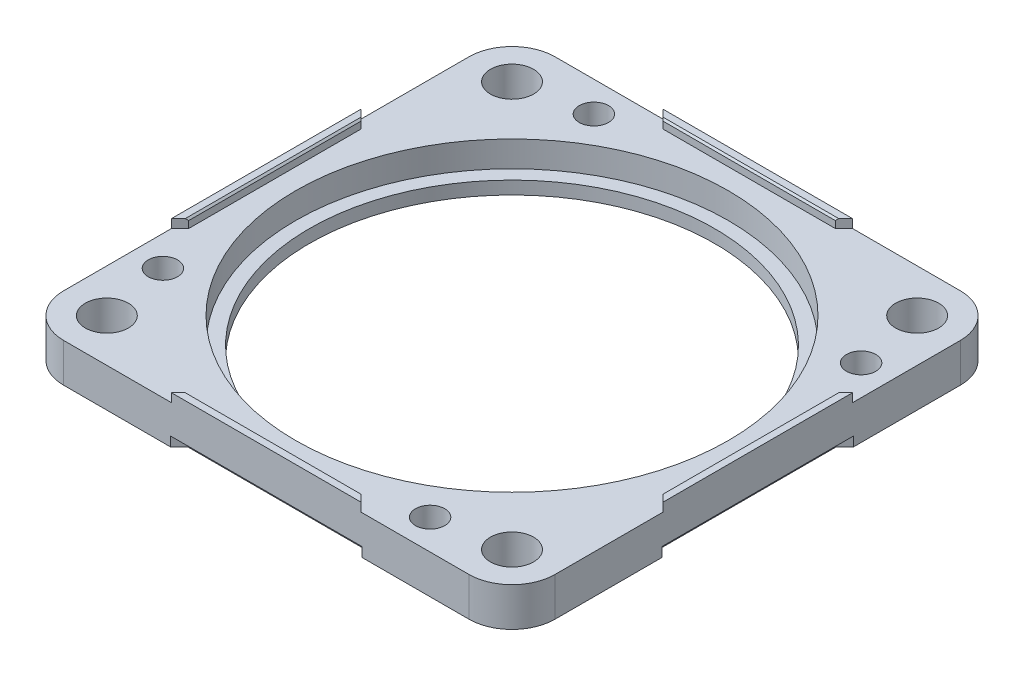
SolidWorks part; units mm, degrees
ref_plane "前视基准面" through (0, 0, 0) normal (0, 0, 1) x (1, 0, 0)
ref_plane "上视基准面" through (0, 0, 0) normal (0, 1, 0) x (1, 0, 0)
ref_plane "右视基准面" through (0, 0, 0) normal (1, 0, 0) x (0, 0, -1)
sketch "草图1" plane through (0, 0, 0) normal (0, 1, 0) x (1, 0, 0)
  line L1 (-28.5, -28.5) -> (28.5, -28.5)
  line L2 (-28.5, -28.5) -> (-28.5, 28.5)
  line L3 (-28.5, 28.5) -> (28.5, 28.5)
  line L4 (28.5, -28.5) -> (28.5, 28.5)
  line L5 (-28.5, -28.5) -> (28.5, 28.5) construction
  line L6 (-28.5, 28.5) -> (28.5, -28.5) construction
  point P0 (0, 0)
  dimension "D1" = 57
extrude "凸台-拉伸1" add sketch "草图1" along normal blind 4.5
fillet "圆角1" radius 5 4 edges at (-28.5, 2.25, -28.5) (-28.5, 2.25, 28.5) (28.5, 2.25, 28.5) (28.5, 2.25, -28.5)
sketch "草图2" plane through (0, 4.5, 0) normal (0, 1, 0) x (1, 0, 0)
  circle A0 centre (0, 0) radius 25.1
  dimension "D1" = 50.2
extrude "切除-拉伸1" cut sketch "草图2" against normal blind 3
sketch "草图3" plane through (0, 1.5, 0) normal (0, 1, 0) x (1, 0, 0)
  circle A0 centre (0, 0) radius 23.5
  dimension "D1" = 47
extrude "切除-拉伸2" cut sketch "草图3" against normal blind 1.5
sketch "草图4" plane through (0, 4.5, 0) normal (0, 1, 0) x (1, 0, 0)
  line L0 (23.5, 28.5) -> (-23.5, 28.5) construction
  line L1 (-23.5, 23.5) -> (0, 0) construction
  line L2 (0, 0) -> (0, -50000) construction
  circle A0 centre (-23.5, 23.5) radius 2.5
  circle A1 centre (-15.5, 25) radius 1.7
  dimension "D1" = 3.4
  dimension "D2" = 5
  dimension "D4" = 8
  dimension "D6" = 47
  dimension "D3" = 3.5
  dimension "D5" = 45
extrude "切除-拉伸3" cut sketch "草图4" against normal blind 4.5
sketch "草图5" plane through (0, 4.5, 0) normal (0, 1, 0) x (1, 0, 0)
  line L0 (-28.5, 11) -> (-28.5, -11)
  line L1 (-28.5, 23.5) -> (-28.5, -23.5) construction
  line L2 (-28.5, -11) -> (-27.5, -10)
  line L3 (-27.5, -10) -> (-27.5, 10)
  line L4 (-27.5, 10) -> (-28.5, 11)
  line L5 (-27.5, 0) -> (0, 0) construction
  dimension "D1" = 135
  dimension "D2" = 135
  dimension "D3" = 22
  dimension "D4" = 1
extrude "凸台-拉伸2" add sketch "草图5" along normal blind 1
chamfer "倒角1" distance 0.2 angle 45 1 edges at (-27.5, 5.5, 0)
sketch "草图6" plane through (0, 0, 0) normal (0, -1, 0) x (1, 0, 0)
  line L0 (-28.5, 11.1) -> (-28.5, -11.1)
  line L1 (-28.5, -23.5) -> (-28.5, 23.5) construction
  line L2 (-28.5, -11.1) -> (-27.5, -10.1)
  line L3 (-27.5, -10.1) -> (-27.5, 10.1)
  line L4 (-27.5, 10.1) -> (-28.5, 11.1)
  line L5 (-27.5, 0) -> (0, 0) construction
  dimension "D1" = 135
  dimension "D2" = 135
  dimension "D3" = 1
  dimension "D4" = 22.2
extrude "切除-拉伸4" cut sketch "草图6" against normal blind 1.1
pattern_circular "阵列(圆周)1" count 4 over 360 about axis through (0, 0, 0) along (0, 1, 0) of "切除-拉伸3", "切除-拉伸4", "凸台-拉伸2", "倒角1"
